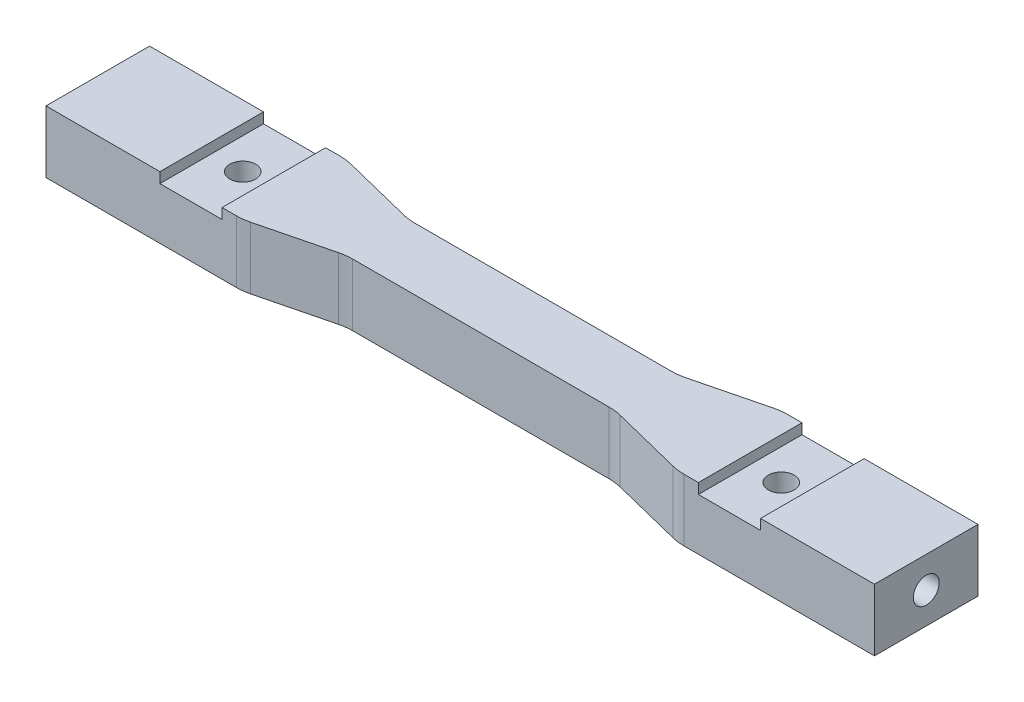
SolidWorks part; units mm, degrees
material "1060 Alloy"
ref_plane "Front Plane" through (0, 0, 0) normal (0, 0, 1) x (1, 0, 0)
ref_plane "Top Plane" through (0, 0, 0) normal (0, 1, 0) x (1, 0, 0)
ref_plane "Right Plane" through (0, 0, 0) normal (1, 0, 0) x (0, 0, -1)
sketch "Sketch1" plane through (0, 0, 0) normal (0, 1, 0) x (1, 0, 0)
  line L1 (0, 0) -> (80, 0)
  line L2 (0, 0) -> (0, 10)
  line L3 (0, 10) -> (80, 10)
  line L4 (80, 0) -> (80, 10)
  dimension "D1" = 10
  dimension "D2" = 80
extrude "Boss-Extrude1" add sketch "Sketch1" along normal blind 6
sketch "Sketch2" plane through (0, 6, 0) normal (0, 1, 0) x (1, 0, 0)
  line L0 (80, 10) -> (0, 10) construction
  line L1 (11, 10) -> (17, 10)
  line L2 (11, 10) -> (11, 0)
  line L3 (11, 0) -> (17, 0)
  line L4 (17, 10) -> (17, 0)
  line L5 (0, 0) -> (80, 0) construction
  line L7 (69, 10) -> (63, 10)
  line L8 (69, 10) -> (69, 0)
  line L9 (69, 0) -> (63, 0)
  line L10 (63, 10) -> (63, 0)
  line L11 (0, 10) -> (0, 0) construction
  line L12 (80, 0) -> (80, 10) construction
  dimension "D1" = 11
  dimension "D2" = 11
  dimension "D3" = 6
extrude "Cut-Extrude1" cut sketch "Sketch2" against normal blind 1
hole_wizard "Tap Drill for M3x0.5 Tap1" positions "3DSketch1" profile "Sketch5" hole size "M3x0.5" standard "ANSI Metric"
sketch3d "3DSketch1"
  line L0 (0, 0, -10) -> (0, 0, 0) construction
  line L1 (80, 0, -10) -> (0, 0, -10) construction
  line L2 (0, 6, 0) -> (0, 0, 0) construction
  line L3 (80, 0, 0) -> (80, 0, -10) construction
  line L4 (80, 6, 0) -> (80, 0, 0) construction
  point P0 (80, 3, -5)
  point P2 (66, 0, -5)
  point P4 (14, 0, -5)
  point P6 (0, 3, -5)
  dimension "D1" = 14
  dimension "D2" = 5
  dimension "D3" = 3
  dimension "D4" = 5
  dimension "D5" = 14
  dimension "D6" = 5
  dimension "D7" = 5
  dimension "D8" = 3
sketch "Sketch5" plane through (80, 3, -5) normal (0, 1, 0) x (0, 0, -1)
  line L0 (0, 0) -> (0, 10.7511)
  line L1 (0, 10.7511) -> (1.25, 10)
  line L2 (1.25, 10) -> (1.25, 0)
  line L5 (1.25, 0) -> (0, 0)
  line L10 (0, 10.7511) -> (-1.25, 10) construction
  line L11 (0, -6.35) -> (0, 107.95) construction
  dimension "Hole Dia." = 2.5
  dimension "Hole Depth" = 10
  dimension "Drill Angle" = 118
chamfer "Chamfer1" distance 1.5 angle 45 2 edges at (66, 0, -6.25) (14, 0, -6.25)
sketch "Sketch6" plane through (0, 6, 0) normal (0, 1, 0) x (1, 0, 0)
  line L0 (19, 10) -> (27, 8)
  line L1 (63, 10) -> (17, 10) construction
  line L2 (27, 8) -> (53, 8)
  line L3 (53, 8) -> (61, 10)
  line L4 (61, 10) -> (19, 10)
  line L5 (19, 0) -> (27, 2)
  line L6 (17, 0) -> (63, 0) construction
  line L7 (27, 2) -> (53, 2)
  line L8 (53, 2) -> (61, 0)
  line L9 (61, 0) -> (19, 0)
  line L10 (17, 0) -> (17, 10) construction
  line L11 (63, 10) -> (63, 0) construction
  dimension "D1" = 6
  dimension "D2" = 2
  dimension "D3" = 2
  dimension "D4" = 8
extrude "Cut-Extrude2" cut sketch "Sketch6" against normal up to next
fillet "Fillet1" radius 5 8 edges at (61, 3, 0) (53, 3, -2) (27, 3, -2) (19, 3, 0) (61, 3, -10) (53, 3, -8) (27, 3, -8) (19, 3, -10)
